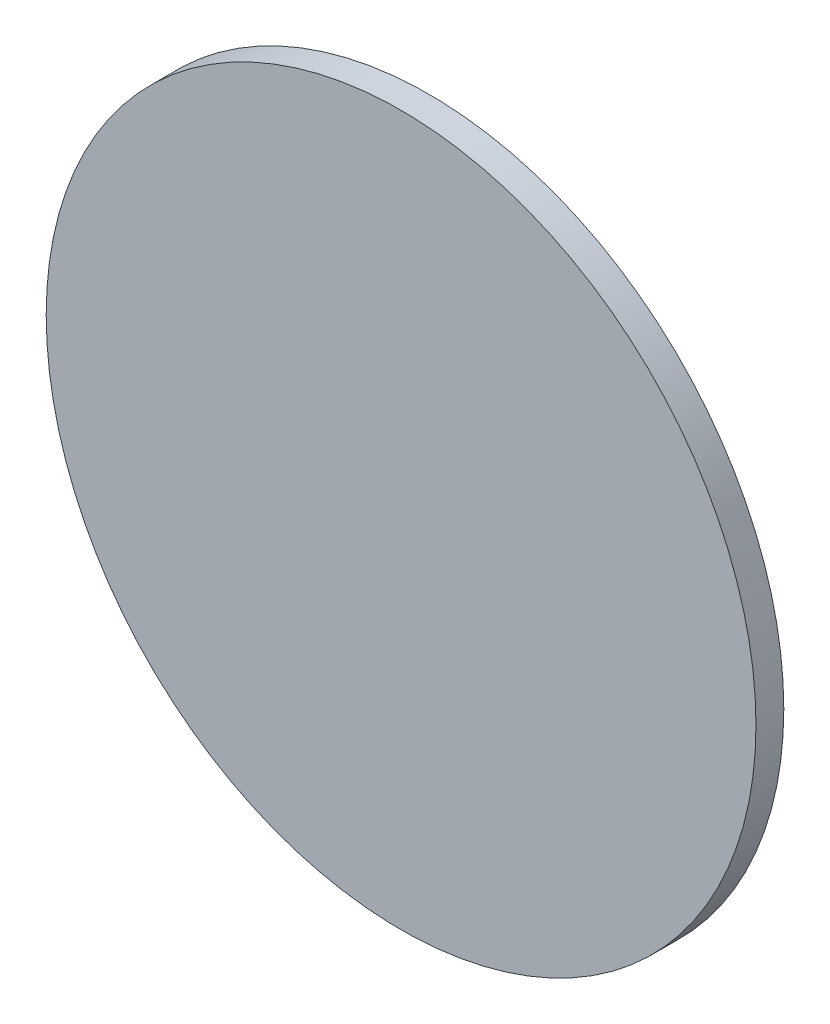
SolidWorks part; units mm, degrees
ref_plane "正面" through (0, 0, 0) normal (0, 0, 1) x (1, 0, 0)
ref_plane "平面" through (0, 0, 0) normal (0, 1, 0) x (1, 0, 0)
ref_plane "右側面" through (0, 0, 0) normal (1, 0, 0) x (0, 0, -1)
sketch "ｽｹｯﾁ2" plane through (0, 0, 0) normal (0, 0, 1) x (1, 0, 0)
  circle A0 centre (0, 0) radius 127.5
  dimension "D1" = 255
extrude "ﾎﾞｽ - 押し出し1" add sketch "ｽｹｯﾁ2" along normal blind 10
